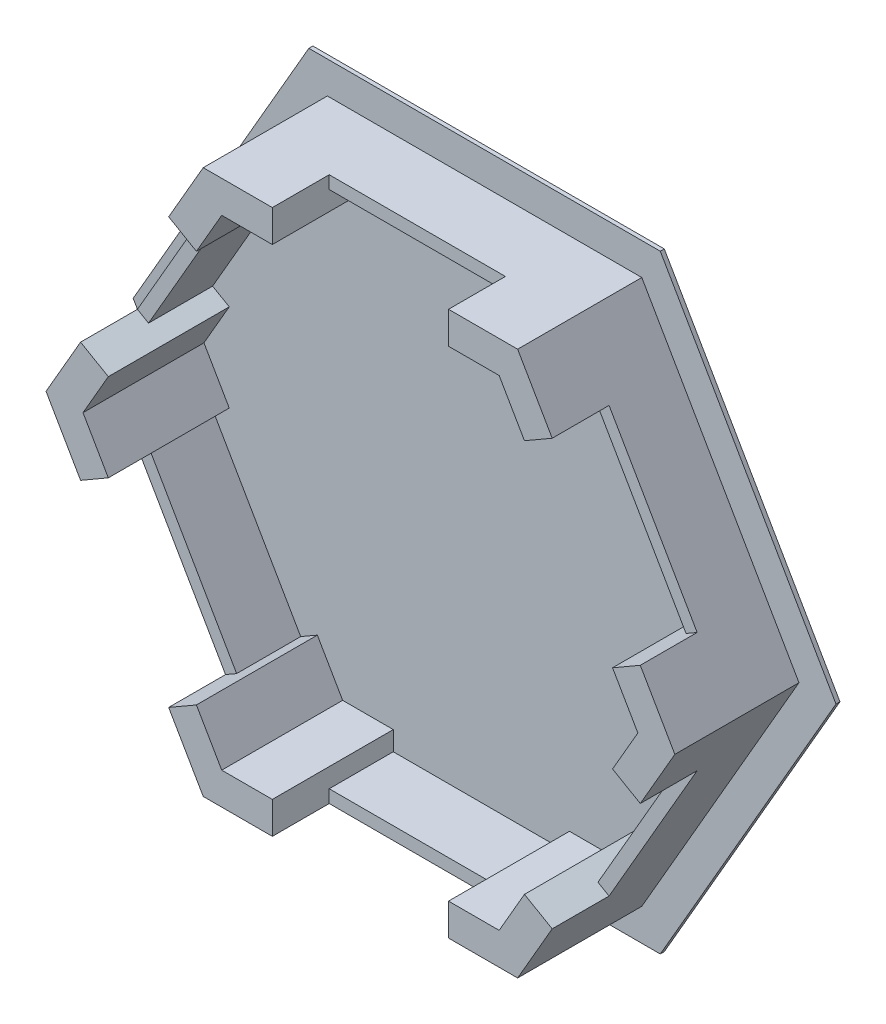
SolidWorks part; units mm, degrees
ref_plane "Спереди" through (0, 0, 0) normal (0, 0, 1) x (1, 0, 0)
ref_plane "Сверху" through (0, 0, 0) normal (0, 1, 0) x (1, 0, 0)
ref_plane "Справа" through (0, 0, 0) normal (1, 0, 0) x (0, 0, -1)
sketch "Sketch1" plane through (0, 0, 0) normal (0, 0, 1) x (1, 0, 0)
  line L2 (19.6299, 0) -> (9.815, 17)
  line L3 (9.815, 17) -> (-9.815, 17)
  line L4 (-9.815, 17) -> (-19.6299, 0)
  line L5 (-19.6299, 0) -> (-9.815, -17)
  line L6 (-9.815, -17) -> (9.815, -17)
  line L7 (9.815, -17) -> (19.6299, 0)
  circle A0 centre (0, 0) radius 17 construction
  dimension "D1" = 34
extrude "Boss-Extrude1" add sketch "Sketch1" along normal blind 0.45 contours L4 L5 L6 L7 L2 L3
sketch "Sketch2" plane through (0, 0, 0) normal (0, 0, 1) x (1, 0, 0)
  line L0 (9.815, 17) -> (-9.815, 17) construction
  line L1 (-5.5, 17.5) -> (5.5, 17.5)
  line L2 (-5.5, 17.5) -> (-5.5, 17)
  line L3 (-5.5, 17) -> (5.5, 17)
  line L4 (5.5, 17.5) -> (5.5, 17)
  line L5 (-5.5, 17.5) -> (5.5, 17) construction
  line L6 (-5.5, 17) -> (5.5, 17.5) construction
  line L7 (12.4054, 13.5131) -> (17.9054, 3.9869)
  line L8 (12.4054, 13.5131) -> (11.9724, 13.2631)
  line L9 (11.9724, 13.2631) -> (17.4724, 3.7369)
  line L10 (17.9054, 3.9869) -> (17.4724, 3.7369)
  line L11 (12.4054, 13.5131) -> (17.4724, 3.7369) construction
  line L12 (11.9724, 13.2631) -> (17.9054, 3.9869) construction
  line L13 (17.9054, -3.9869) -> (12.4054, -13.5131)
  line L14 (17.9054, -3.9869) -> (17.4724, -3.7369)
  line L15 (17.4724, -3.7369) -> (11.9724, -13.2631)
  line L16 (12.4054, -13.5131) -> (11.9724, -13.2631)
  line L17 (17.9054, -3.9869) -> (11.9724, -13.2631) construction
  line L18 (17.4724, -3.7369) -> (12.4054, -13.5131) construction
  line L19 (5.5, -17.5) -> (-5.5, -17.5)
  line L20 (5.5, -17.5) -> (5.5, -17)
  line L21 (5.5, -17) -> (-5.5, -17)
  line L22 (-5.5, -17.5) -> (-5.5, -17)
  line L23 (5.5, -17.5) -> (-5.5, -17) construction
  line L24 (5.5, -17) -> (-5.5, -17.5) construction
  line L25 (-12.4054, -13.5131) -> (-17.9054, -3.9869)
  line L26 (-12.4054, -13.5131) -> (-11.9724, -13.2631)
  line L27 (-11.9724, -13.2631) -> (-17.4724, -3.7369)
  line L28 (-17.9054, -3.9869) -> (-17.4724, -3.7369)
  line L29 (-12.4054, -13.5131) -> (-17.4724, -3.7369) construction
  line L30 (-11.9724, -13.2631) -> (-17.9054, -3.9869) construction
  line L31 (-17.9054, 3.9869) -> (-12.4054, 13.5131)
  line L32 (-17.9054, 3.9869) -> (-17.4724, 3.7369)
  line L33 (-17.4724, 3.7369) -> (-11.9724, 13.2631)
  line L34 (-12.4054, 13.5131) -> (-11.9724, 13.2631)
  line L35 (-17.9054, 3.9869) -> (-11.9724, 13.2631) construction
  line L36 (-17.4724, 3.7369) -> (-12.4054, 13.5131) construction
  point P0 (0, 17.25)
  point P8 (14.9389, 8.625)
  point P16 (14.9389, -8.625)
  point P21 (0, -17.25)
  point P26 (-14.9389, -8.625)
  point P31 (-14.9389, 8.625)
  point P36 (0, 0)
  dimension "D1" = 0.5
  dimension "D2" = 11
  dimension "D3" = 6
extrude "Boss-Extrude2" add sketch "Sketch2" along normal blind 0.25
sketch "Sketch3" plane through (0, 0, 0) normal (0, 0, 1) x (1, 0, 0)
  line L0 (9.815, 17) -> (-9.815, 17) construction
  line L1 (-5.5, 17.5) -> (-5.5, 17) construction
  line L2 (-11.9724, 13.2631) -> (-12.4054, 13.5131) construction
  line L3 (-11.9724, 13.2631) -> (-10.2404, 12.2631)
  line L4 (5.5, 17) -> (5.5, 15)
  line L5 (5.5, 15) -> (8.6603, 15)
  line L6 (7.5, 17) -> (9.815, 17)
  line L7 (9.815, 17) -> (10.9724, 14.9952)
  line L8 (-10.2404, 12.2631) -> (-8.6603, 15)
  line L9 (11.9724, 13.2631) -> (10.2404, 12.2631)
  line L10 (-17.4724, 3.7369) -> (-11.9724, 13.2631) construction
  line L13 (10.2404, 12.2631) -> (8.6603, 15)
  line L14 (10.9724, 14.9952) -> (11.9724, 13.2631)
  line L15 (7.5, 17) -> (5.5, 17)
  line L16 (17.4724, 3.7369) -> (15.7404, 2.7369)
  line L17 (15.7404, 2.7369) -> (17.3205, 0)
  line L18 (18.4724, 2.0048) -> (19.6299, 0)
  line L19 (19.6299, 0) -> (18.4724, -2.0048)
  line L20 (17.4724, -3.7369) -> (15.7404, -2.7369)
  line L21 (15.7404, -2.7369) -> (17.3205, 0)
  line L22 (18.4724, -2.0048) -> (17.4724, -3.7369)
  line L23 (18.4724, 2.0048) -> (17.4724, 3.7369)
  line L24 (11.9724, -13.2631) -> (10.2404, -12.2631)
  line L25 (10.2404, -12.2631) -> (8.6603, -15)
  line L26 (10.9724, -14.9952) -> (9.815, -17)
  line L27 (9.815, -17) -> (7.5, -17)
  line L28 (5.5, -17) -> (5.5, -15)
  line L29 (5.5, -15) -> (8.6603, -15)
  line L30 (7.5, -17) -> (5.5, -17)
  line L31 (10.9724, -14.9952) -> (11.9724, -13.2631)
  line L32 (-5.5, -17) -> (-5.5, -15)
  line L33 (-5.5, -15) -> (-8.6603, -15)
  line L34 (-7.5, -17) -> (-9.815, -17)
  line L35 (-9.815, -17) -> (-10.9724, -14.9952)
  line L36 (-11.9724, -13.2631) -> (-10.2404, -12.2631)
  line L37 (-10.2404, -12.2631) -> (-8.6603, -15)
  line L38 (-10.9724, -14.9952) -> (-11.9724, -13.2631)
  line L39 (-7.5, -17) -> (-5.5, -17)
  line L40 (-17.4724, -3.7369) -> (-15.7404, -2.7369)
  line L41 (-15.7404, -2.7369) -> (-17.3205, 0)
  line L42 (-18.4724, -2.0048) -> (-19.6299, 0)
  line L43 (-19.6299, 0) -> (-18.4724, 2.0048)
  line L44 (-17.4724, 3.7369) -> (-15.7404, 2.7369)
  line L45 (-15.7404, 2.7369) -> (-17.3205, 0)
  line L46 (-18.4724, 2.0048) -> (-17.4724, 3.7369)
  line L47 (-18.4724, -2.0048) -> (-17.4724, -3.7369)
  line L49 (-10.9724, 14.9952) -> (-9.815, 17)
  line L50 (-9.815, 17) -> (-7.5, 17)
  line L51 (-5.5, 17) -> (-5.5, 15)
  line L52 (-5.5, 15) -> (-8.6603, 15)
  line L76 (-7.5, 17) -> (-5.5, 17)
  line L77 (-10.9724, 14.9952) -> (-11.9724, 13.2631)
  point P60 (0, 0)
  point P85 (0, 0)
  dimension "D1" = 2
extrude "Boss-Extrude3" add sketch "Sketch3" along normal blind 8
sketch "Sketch4" plane through (0, 0, 0) normal (0, 0, 1) x (1, 0, 0)
  line L1 (21.9393, 0) -> (10.9697, 19)
  line L2 (10.9697, 19) -> (-10.9697, 19)
  line L3 (-10.9697, 19) -> (-21.9393, 0)
  line L4 (-21.9393, 0) -> (-10.9697, -19)
  line L5 (-10.9697, -19) -> (10.9697, -19)
  line L6 (10.9697, -19) -> (21.9393, 0)
  circle A0 centre (0, 0) radius 19 construction
  dimension "D1" = 38
extrude "Boss-Extrude4" add sketch "Sketch4" along normal blind 0.25
sketch "Sketch5" plane through (0, 0, 0.45) normal (0, 0, 1) x (1, 0, 0)
  line L0 (5.5, 15) -> (5.5, 17) construction
  line L1 (-5.5, 17) -> (5.5, 17)
  line L2 (-5.5, 17) -> (-5.5, 16.2)
  line L3 (-5.5, 16.2) -> (5.5, 16.2)
  line L4 (5.5, 17) -> (5.5, 16.2)
  line L5 (11.9724, 13.2631) -> (17.4724, 3.7369)
  line L6 (11.9724, 13.2631) -> (11.2796, 12.8631)
  line L7 (11.2796, 12.8631) -> (16.7796, 3.3369)
  line L8 (17.4724, 3.7369) -> (16.7796, 3.3369)
  line L9 (17.4724, -3.7369) -> (11.9724, -13.2631)
  line L10 (17.4724, -3.7369) -> (16.7796, -3.3369)
  line L11 (16.7796, -3.3369) -> (11.2796, -12.8631)
  line L12 (11.9724, -13.2631) -> (11.2796, -12.8631)
  line L13 (5.5, -17) -> (-5.5, -17)
  line L14 (5.5, -17) -> (5.5, -16.2)
  line L15 (5.5, -16.2) -> (-5.5, -16.2)
  line L16 (-5.5, -17) -> (-5.5, -16.2)
  line L17 (-11.9724, -13.2631) -> (-17.4724, -3.7369)
  line L18 (-11.9724, -13.2631) -> (-11.2796, -12.8631)
  line L19 (-11.2796, -12.8631) -> (-16.7796, -3.3369)
  line L20 (-17.4724, -3.7369) -> (-16.7796, -3.3369)
  line L21 (-17.4724, 3.7369) -> (-11.9724, 13.2631)
  line L22 (-17.4724, 3.7369) -> (-16.7796, 3.3369)
  line L23 (-16.7796, 3.3369) -> (-11.2796, 12.8631)
  line L24 (-11.9724, 13.2631) -> (-11.2796, 12.8631)
  point P7 (0, 0)
  point P30 (0, 0)
  dimension "D1" = 0.8
extrude "Boss-Extrude5" add sketch "Sketch5" along normal blind 4
